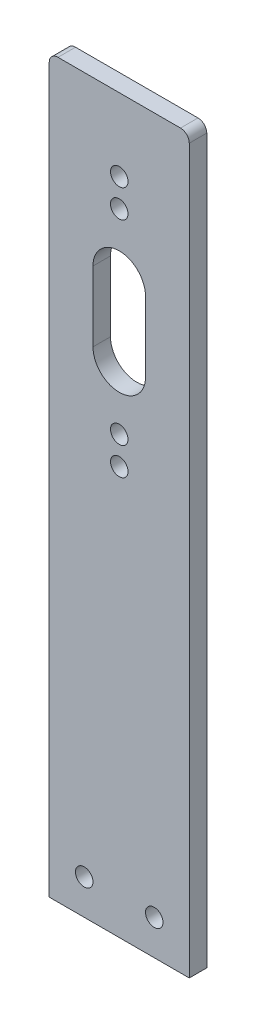
SolidWorks part; units mm, degrees
material "Cast Alloy Steel"
ref_plane "Front Plane" through (0, 0, 0) normal (0, 0, 1) x (1, 0, 0)
ref_plane "Top Plane" through (0, 0, 0) normal (0, 1, 0) x (1, 0, 0)
ref_plane "Right Plane" through (0, 0, 0) normal (1, 0, 0) x (0, 0, -1)
sketch "Sketch1" plane through (0, 0, 0) normal (0, 0, 1) x (1, 0, 0)
  line L0 (-25.4, -132.715) -> (25.4, -132.715)
  line L1 (-25.4, -132.715) -> (-25.4, 132.715)
  line L2 (-25.4, 132.715) -> (25.4, 132.715)
  line L3 (25.4, -132.715) -> (25.4, 132.715)
  line L4 (0, 0) -> (25.4, 0) construction
  line L5 (0, 0) -> (0, 132.715) construction
  line L6 (9.525, 73.4987) -> (9.525, 48.0987)
  line L7 (-9.525, 48.0987) -> (-9.525, 73.4987)
  line L8 (9.525, 60.7987) -> (0, 60.7987) construction
  circle A0 centre (0, 106.3574) radius 3.175
  circle A1 centre (0, 96.1974) radius 3.175
  circle A2 centre (0, 15.24) radius 3.175
  circle A3 centre (0, 25.4) radius 3.175
  circle A4 centre (12.7, -120.015) radius 3.175
  circle A5 centre (-12.7, -120.015) radius 3.175
  arc A6 (-9.525, 48.0987) -> (9.525, 48.0987) centre (0, 48.0987) ccw
  arc A7 (9.525, 73.4987) -> (-9.525, 73.4987) centre (0, 73.4987) ccw
  point P25 (0, 60.7987)
  dimension "D3" = 6.35
  dimension "D4" = 6.35
  dimension "D5" = 6.35
  dimension "D8" = 9.525
  dimension "D1" = 50.8
  dimension "D2" = 265.43
  dimension "D6" = 70.7974
  dimension "D7" = 10.16
  dimension "D9" = 25.4
  dimension "D10" = 15.24
  dimension "D12" = 10.16
  dimension "D13" = 12.7
  dimension "D14" = 25.4
extrude "Extrude1" add sketch "Sketch1" along normal mid plane 6.35
fillet "Fillet1" radius 3.175 2 edges at (25.4, 132.715, 0) (-25.4, 132.715, 0)
ref_plane "Plane1" through (0, 60.7987, 0) normal (0, 1, 0) x (-1, 0, 0)
